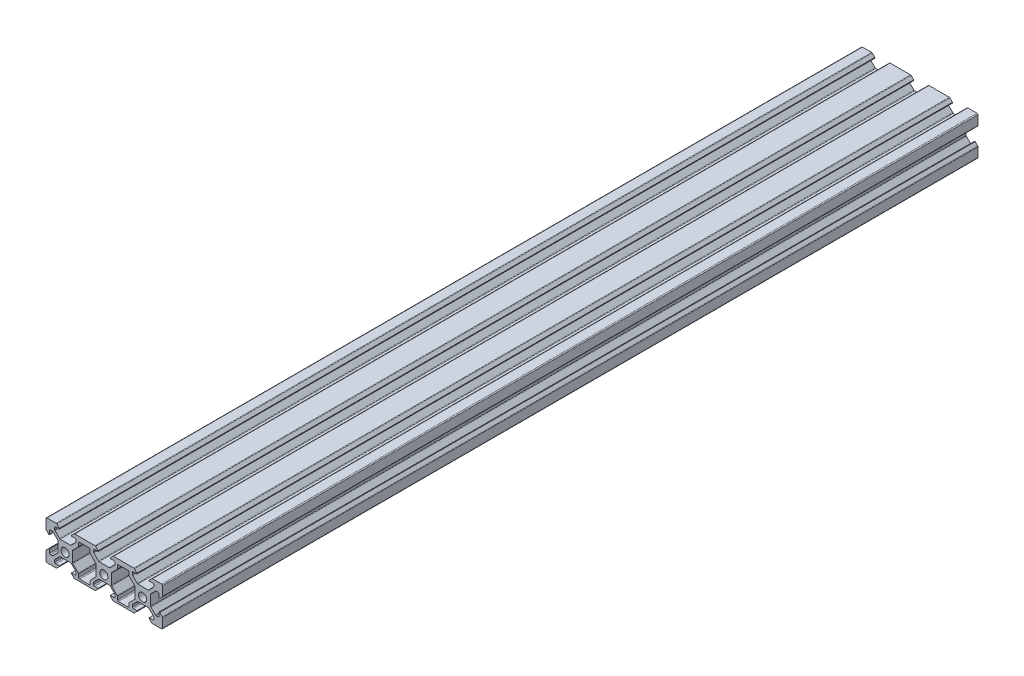
SolidWorks part; units mm, degrees
ref_plane "Front Plane" through (0, 0, 0) normal (0, 0, 1) x (1, 0, 0)
ref_plane "Top Plane" through (0, 0, 0) normal (0, 1, 0) x (1, 0, 0)
ref_plane "Right Plane" through (0, 0, 0) normal (1, 0, 0) x (0, 0, -1)
sketch "Sketch1" plane through (0, 0, 0) normal (0, 0, 1) x (1, 0, 0)
  line L24 (-13, 7.7) -> (-13, 6.1464)
  line L25 (-12.5, 8.2) -> (-7.5, 8.2)
  line L26 (-7, 6.1464) -> (-7, 7.7)
  line L27 (-6.8536, 5.7929) -> (-4.0464, 2.9858)
  line L28 (-3.9, 2.6322) -> (-3.9, -2.6322)
  line L29 (-15.9536, 2.9858) -> (-13.1464, 5.7929)
  line L30 (-16.1, -2.6322) -> (-16.1, 2.6322)
  line L31 (-13.1464, -5.7929) -> (-15.9536, -2.9858)
  line L32 (-13, -6.1464) -> (-13, -7.7)
  line L33 (-7.5, -8.2) -> (-12.5, -8.2)
  line L34 (-7, -7.7) -> (-7, -6.1464)
  line L35 (-4.0464, -2.9858) -> (-6.8536, -5.7929)
  line L36 (12.5, -8.2) -> (7.5, -8.2)
  line L37 (7, -6.1464) -> (7, -7.7)
  line L38 (6.8536, -5.7929) -> (4.0464, -2.9858)
  line L39 (3.9, -2.6322) -> (3.9, 2.6322)
  line L40 (4.0464, 2.9858) -> (6.8536, 5.7929)
  line L41 (7, 7.7) -> (7, 6.1464)
  line L42 (7.5, 8.2) -> (12.5, 8.2)
  line L43 (13, 6.1464) -> (13, 7.7)
  line L44 (13.1464, 5.7929) -> (15.9536, 2.9858)
  line L45 (16.1, 2.6322) -> (16.1, -2.6322)
  line L46 (15.9536, -2.9858) -> (13.1464, -5.7929)
  line L47 (13, -7.7) -> (13, -6.1464)
  line L200 (-22.4092, -3.2009) -> (-17.1447, -3.2009)
  line L201 (-16.7912, -3.3473) -> (-14.4234, -5.7151)
  line L202 (-14.277, -6.0686) -> (-14.277, -7.0009)
  line L203 (-14.777, -7.5009) -> (-16.652, -7.5009)
  line L204 (-16.652, -7.5009) -> (-16.652, -7.8459)
  line L205 (-16.652, -7.8459) -> (-15.3434, -9.1544)
  line L206 (-14.9898, -9.3009) -> (-4.5641, -9.3009)
  line L207 (-4.2105, -9.1544) -> (-2.902, -7.8459)
  line L208 (-2.902, -7.8459) -> (-2.902, -7.5009)
  line L209 (-2.902, -7.5009) -> (-4.777, -7.5009)
  line L210 (-5.277, -7.0009) -> (-5.277, -6.0686)
  line L211 (-5.1305, -5.7151) -> (-2.7627, -3.3473)
  line L212 (-2.4092, -3.2009) -> (2.8553, -3.2009)
  line L213 (3.2088, -3.3473) -> (5.5766, -5.7151)
  line L214 (5.723, -6.0686) -> (5.723, -7.0009)
  line L215 (5.223, -7.5009) -> (3.348, -7.5009)
  line L216 (3.348, -7.5009) -> (3.348, -7.8459)
  line L217 (3.348, -7.8459) -> (4.6566, -9.1544)
  line L218 (5.0102, -9.3009) -> (15.4359, -9.3009)
  line L219 (15.7895, -9.1544) -> (17.098, -7.8459)
  line L220 (17.098, -7.8459) -> (17.098, -7.5009)
  line L221 (17.098, -7.5009) -> (15.223, -7.5009)
  line L222 (14.723, -7.0009) -> (14.723, -6.0686)
  line L223 (14.8695, -5.7151) -> (17.2373, -3.3473)
  line L224 (17.5908, -3.2009) -> (22.8553, -3.2009)
  line L225 (23.2088, -3.3473) -> (25.5766, -5.7151)
  line L226 (25.723, -6.0686) -> (25.723, -7.0009)
  line L227 (25.223, -7.5009) -> (23.348, -7.5009)
  line L228 (23.348, -7.5009) -> (23.348, -7.8459)
  line L229 (23.348, -7.8459) -> (24.6566, -9.1544)
  line L230 (25.0102, -9.3009) -> (29.723, -9.3009)
  line L231 (30.223, -8.8009) -> (30.223, -4.088)
  line L232 (30.0766, -3.7344) -> (28.768, -2.4259)
  line L233 (28.768, -2.4259) -> (28.423, -2.4259)
  line L234 (28.423, -2.4259) -> (28.423, -4.3009)
  line L235 (27.923, -4.8009) -> (26.9908, -4.8009)
  line L236 (26.6373, -4.6544) -> (24.2695, -2.2866)
  line L237 (24.123, -1.9331) -> (24.123, 3.3314)
  line L238 (24.2695, 3.6849) -> (26.6373, 6.0527)
  line L239 (26.9908, 6.1991) -> (27.923, 6.1991)
  line L240 (28.423, 5.6991) -> (28.423, 3.8241)
  line L241 (28.423, 3.8241) -> (28.768, 3.8241)
  line L242 (28.768, 3.8241) -> (30.0766, 5.1327)
  line L243 (30.223, 5.4863) -> (30.223, 10.1991)
  line L244 (29.723, 10.6991) -> (25.0102, 10.6991)
  line L245 (24.6566, 10.5527) -> (23.348, 9.2441)
  line L246 (23.348, 9.2441) -> (23.348, 8.8991)
  line L247 (23.348, 8.8991) -> (25.223, 8.8991)
  line L248 (25.723, 8.3991) -> (25.723, 7.4669)
  line L249 (25.5766, 7.1134) -> (23.2088, 4.7456)
  line L250 (22.8553, 4.5991) -> (17.5908, 4.5991)
  line L251 (17.2373, 4.7456) -> (14.8695, 7.1134)
  line L252 (14.723, 7.4669) -> (14.723, 8.3991)
  line L253 (15.223, 8.8991) -> (17.098, 8.8991)
  line L254 (17.098, 8.8991) -> (17.098, 9.2441)
  line L255 (17.098, 9.2441) -> (15.7895, 10.5527)
  line L256 (15.4359, 10.6991) -> (5.0102, 10.6991)
  line L257 (4.6566, 10.5527) -> (3.348, 9.2441)
  line L258 (3.348, 9.2441) -> (3.348, 8.8991)
  line L259 (3.348, 8.8991) -> (5.223, 8.8991)
  line L260 (5.723, 8.3991) -> (5.723, 7.4669)
  line L261 (5.5766, 7.1134) -> (3.2088, 4.7456)
  line L262 (2.8553, 4.5991) -> (-2.4092, 4.5991)
  line L263 (-2.7627, 4.7456) -> (-5.1305, 7.1134)
  line L264 (-5.277, 7.4669) -> (-5.277, 8.3991)
  line L265 (-4.777, 8.8991) -> (-2.902, 8.8991)
  line L266 (-2.902, 8.8991) -> (-2.902, 9.2441)
  line L267 (-2.902, 9.2441) -> (-4.2105, 10.5527)
  line L268 (-4.5641, 10.6991) -> (-14.9898, 10.6991)
  line L269 (-15.3434, 10.5527) -> (-16.652, 9.2441)
  line L270 (-16.652, 9.2441) -> (-16.652, 8.8991)
  line L271 (-16.652, 8.8991) -> (-14.777, 8.8991)
  line L272 (-14.277, 8.3991) -> (-14.277, 7.4669)
  line L273 (-14.4234, 7.1134) -> (-16.7912, 4.7456)
  line L274 (-17.1447, 4.5991) -> (-22.4092, 4.5991)
  line L275 (-22.7627, 4.7456) -> (-25.1305, 7.1134)
  line L276 (-25.277, 7.4669) -> (-25.277, 8.3991)
  line L277 (-24.777, 8.8991) -> (-22.902, 8.8991)
  line L278 (-22.902, 8.8991) -> (-22.902, 9.2441)
  line L279 (-22.902, 9.2441) -> (-24.2105, 10.5527)
  line L280 (-24.5641, 10.6991) -> (-29.277, 10.6991)
  line L281 (-29.777, 10.1991) -> (-29.777, 5.4863)
  line L282 (-29.6305, 5.1327) -> (-28.322, 3.8241)
  line L283 (-28.322, 3.8241) -> (-27.977, 3.8241)
  line L284 (-27.977, 3.8241) -> (-27.977, 5.6991)
  line L285 (-27.477, 6.1991) -> (-26.5447, 6.1991)
  line L286 (-26.1912, 6.0527) -> (-23.8234, 3.6849)
  line L287 (-23.677, 3.3314) -> (-23.677, -1.9331)
  line L288 (-23.8234, -2.2866) -> (-26.1912, -4.6544)
  line L289 (-26.5447, -4.8009) -> (-27.477, -4.8009)
  line L290 (-27.977, -4.3009) -> (-27.977, -2.4259)
  line L291 (-27.977, -2.4259) -> (-28.322, -2.4259)
  line L292 (-28.322, -2.4259) -> (-29.6305, -3.7344)
  line L293 (-29.777, -4.088) -> (-29.777, -8.8009)
  line L294 (-29.277, -9.3009) -> (-24.5641, -9.3009)
  line L295 (-24.2105, -9.1544) -> (-22.902, -7.8459)
  line L296 (-22.902, -7.8459) -> (-22.902, -7.5009)
  line L297 (-22.902, -7.5009) -> (-24.777, -7.5009)
  line L298 (-25.277, -7.0009) -> (-25.277, -6.0686)
  line L299 (-25.1305, -5.7151) -> (-22.7627, -3.3473)
  arc A27 (-13.1464, 5.7929) -> (-13, 6.1464) centre (-13.5, 6.1464) ccw
  arc A28 (-12.5, 8.2) -> (-13, 7.7) centre (-12.5, 7.7) ccw
  arc A29 (-7, 7.7) -> (-7.5, 8.2) centre (-7.5, 7.7) ccw
  arc A30 (-7, 6.1464) -> (-6.8536, 5.7929) centre (-6.5, 6.1464) ccw
  arc A31 (-3.9, 2.6322) -> (-4.0464, 2.9858) centre (-4.4, 2.6322) ccw
  arc A32 (-15.9536, 2.9858) -> (-16.1, 2.6322) centre (-15.6, 2.6322) ccw
  circle A33 centre (-20, 0) radius 2.1
  arc A34 (-16.1, -2.6322) -> (-15.9536, -2.9858) centre (-15.6, -2.6322) ccw
  arc A35 (-13, -6.1464) -> (-13.1464, -5.7929) centre (-13.5, -6.1464) ccw
  arc A36 (-13, -7.7) -> (-12.5, -8.2) centre (-12.5, -7.7) ccw
  arc A37 (-7.5, -8.2) -> (-7, -7.7) centre (-7.5, -7.7) ccw
  arc A38 (-6.8536, -5.7929) -> (-7, -6.1464) centre (-6.5, -6.1464) ccw
  arc A39 (-4.0464, -2.9858) -> (-3.9, -2.6322) centre (-4.4, -2.6322) ccw
  circle A40 centre (0, 0) radius 2.1
  arc A41 (7, -7.7) -> (7.5, -8.2) centre (7.5, -7.7) ccw
  arc A42 (7, -6.1464) -> (6.8536, -5.7929) centre (6.5, -6.1464) ccw
  arc A43 (3.9, -2.6322) -> (4.0464, -2.9858) centre (4.4, -2.6322) ccw
  arc A44 (4.0464, 2.9858) -> (3.9, 2.6322) centre (4.4, 2.6322) ccw
  arc A45 (6.8536, 5.7929) -> (7, 6.1464) centre (6.5, 6.1464) ccw
  arc A46 (7.5, 8.2) -> (7, 7.7) centre (7.5, 7.7) ccw
  arc A47 (13, 7.7) -> (12.5, 8.2) centre (12.5, 7.7) ccw
  arc A48 (13, 6.1464) -> (13.1464, 5.7929) centre (13.5, 6.1464) ccw
  arc A49 (16.1, 2.6322) -> (15.9536, 2.9858) centre (15.6, 2.6322) ccw
  arc A50 (15.9536, -2.9858) -> (16.1, -2.6322) centre (15.6, -2.6322) ccw
  arc A51 (13.1464, -5.7929) -> (13, -6.1464) centre (13.5, -6.1464) ccw
  arc A52 (12.5, -8.2) -> (13, -7.7) centre (12.5, -7.7) ccw
  circle A53 centre (20, 0) radius 2.1
  arc A136 (-22.4092, -3.2009) -> (-22.7627, -3.3473) centre (-22.4092, -3.7009) ccw
  arc A137 (-16.7912, -3.3473) -> (-17.1447, -3.2009) centre (-17.1447, -3.7009) ccw
  arc A138 (-14.277, -6.0686) -> (-14.4234, -5.7151) centre (-14.777, -6.0686) ccw
  arc A139 (-14.777, -7.5009) -> (-14.277, -7.0009) centre (-14.777, -7.0009) ccw
  arc A140 (-15.3434, -9.1544) -> (-14.9898, -9.3009) centre (-14.9898, -8.8009) ccw
  arc A141 (-4.5641, -9.3009) -> (-4.2105, -9.1544) centre (-4.5641, -8.8009) ccw
  arc A142 (-5.277, -7.0009) -> (-4.777, -7.5009) centre (-4.777, -7.0009) ccw
  arc A143 (-5.1305, -5.7151) -> (-5.277, -6.0686) centre (-4.777, -6.0686) ccw
  arc A144 (-2.4092, -3.2009) -> (-2.7627, -3.3473) centre (-2.4092, -3.7009) ccw
  arc A145 (3.2088, -3.3473) -> (2.8553, -3.2009) centre (2.8553, -3.7009) ccw
  arc A146 (5.723, -6.0686) -> (5.5766, -5.7151) centre (5.223, -6.0686) ccw
  arc A147 (5.223, -7.5009) -> (5.723, -7.0009) centre (5.223, -7.0009) ccw
  arc A148 (4.6566, -9.1544) -> (5.0102, -9.3009) centre (5.0102, -8.8009) ccw
  arc A149 (15.4359, -9.3009) -> (15.7895, -9.1544) centre (15.4359, -8.8009) ccw
  arc A150 (14.723, -7.0009) -> (15.223, -7.5009) centre (15.223, -7.0009) ccw
  arc A151 (14.8695, -5.7151) -> (14.723, -6.0686) centre (15.223, -6.0686) ccw
  arc A152 (17.5908, -3.2009) -> (17.2373, -3.3473) centre (17.5908, -3.7009) ccw
  arc A153 (23.2088, -3.3473) -> (22.8553, -3.2009) centre (22.8553, -3.7009) ccw
  arc A154 (25.723, -6.0686) -> (25.5766, -5.7151) centre (25.223, -6.0686) ccw
  arc A155 (25.223, -7.5009) -> (25.723, -7.0009) centre (25.223, -7.0009) ccw
  arc A156 (24.6566, -9.1544) -> (25.0102, -9.3009) centre (25.0102, -8.8009) ccw
  arc A157 (29.723, -9.3009) -> (30.223, -8.8009) centre (29.723, -8.8009) ccw
  arc A158 (30.223, -4.088) -> (30.0766, -3.7344) centre (29.723, -4.088) ccw
  arc A159 (27.923, -4.8009) -> (28.423, -4.3009) centre (27.923, -4.3009) ccw
  arc A160 (26.6373, -4.6544) -> (26.9908, -4.8009) centre (26.9908, -4.3009) ccw
  arc A161 (24.123, -1.9331) -> (24.2695, -2.2866) centre (24.623, -1.9331) ccw
  arc A162 (24.2695, 3.6849) -> (24.123, 3.3314) centre (24.623, 3.3314) ccw
  arc A163 (26.9908, 6.1991) -> (26.6373, 6.0527) centre (26.9908, 5.6991) ccw
  arc A164 (28.423, 5.6991) -> (27.923, 6.1991) centre (27.923, 5.6991) ccw
  arc A165 (30.0766, 5.1327) -> (30.223, 5.4863) centre (29.723, 5.4863) ccw
  arc A166 (30.223, 10.1991) -> (29.723, 10.6991) centre (29.723, 10.1991) ccw
  arc A167 (25.0102, 10.6991) -> (24.6566, 10.5527) centre (25.0102, 10.1991) ccw
  arc A168 (25.723, 8.3991) -> (25.223, 8.8991) centre (25.223, 8.3991) ccw
  arc A169 (25.5766, 7.1134) -> (25.723, 7.4669) centre (25.223, 7.4669) ccw
  arc A170 (22.8553, 4.5991) -> (23.2088, 4.7456) centre (22.8553, 5.0991) ccw
  arc A171 (17.2373, 4.7456) -> (17.5908, 4.5991) centre (17.5908, 5.0991) ccw
  arc A172 (14.723, 7.4669) -> (14.8695, 7.1134) centre (15.223, 7.4669) ccw
  arc A173 (15.223, 8.8991) -> (14.723, 8.3991) centre (15.223, 8.3991) ccw
  arc A174 (15.7895, 10.5527) -> (15.4359, 10.6991) centre (15.4359, 10.1991) ccw
  arc A175 (5.0102, 10.6991) -> (4.6566, 10.5527) centre (5.0102, 10.1991) ccw
  arc A176 (5.723, 8.3991) -> (5.223, 8.8991) centre (5.223, 8.3991) ccw
  arc A177 (5.5766, 7.1134) -> (5.723, 7.4669) centre (5.223, 7.4669) ccw
  arc A178 (2.8553, 4.5991) -> (3.2088, 4.7456) centre (2.8553, 5.0991) ccw
  arc A179 (-2.7627, 4.7456) -> (-2.4092, 4.5991) centre (-2.4092, 5.0991) ccw
  arc A180 (-5.277, 7.4669) -> (-5.1305, 7.1134) centre (-4.777, 7.4669) ccw
  arc A181 (-4.777, 8.8991) -> (-5.277, 8.3991) centre (-4.777, 8.3991) ccw
  arc A182 (-4.2105, 10.5527) -> (-4.5641, 10.6991) centre (-4.5641, 10.1991) ccw
  arc A183 (-14.9898, 10.6991) -> (-15.3434, 10.5527) centre (-14.9898, 10.1991) ccw
  arc A184 (-14.277, 8.3991) -> (-14.777, 8.8991) centre (-14.777, 8.3991) ccw
  arc A185 (-14.4234, 7.1134) -> (-14.277, 7.4669) centre (-14.777, 7.4669) ccw
  arc A186 (-17.1447, 4.5991) -> (-16.7912, 4.7456) centre (-17.1447, 5.0991) ccw
  arc A187 (-22.7627, 4.7456) -> (-22.4092, 4.5991) centre (-22.4092, 5.0991) ccw
  arc A188 (-25.277, 7.4669) -> (-25.1305, 7.1134) centre (-24.777, 7.4669) ccw
  arc A189 (-24.777, 8.8991) -> (-25.277, 8.3991) centre (-24.777, 8.3991) ccw
  arc A190 (-24.2105, 10.5527) -> (-24.5641, 10.6991) centre (-24.5641, 10.1991) ccw
  arc A191 (-29.277, 10.6991) -> (-29.777, 10.1991) centre (-29.277, 10.1991) ccw
  arc A192 (-29.777, 5.4863) -> (-29.6305, 5.1327) centre (-29.277, 5.4863) ccw
  arc A193 (-27.477, 6.1991) -> (-27.977, 5.6991) centre (-27.477, 5.6991) ccw
  arc A194 (-26.1912, 6.0527) -> (-26.5447, 6.1991) centre (-26.5447, 5.6991) ccw
  arc A195 (-23.677, 3.3314) -> (-23.8234, 3.6849) centre (-24.177, 3.3314) ccw
  arc A196 (-23.8234, -2.2866) -> (-23.677, -1.9331) centre (-24.177, -1.9331) ccw
  arc A197 (-26.5447, -4.8009) -> (-26.1912, -4.6544) centre (-26.5447, -4.3009) ccw
  arc A198 (-27.977, -4.3009) -> (-27.477, -4.8009) centre (-27.477, -4.3009) ccw
  arc A199 (-29.6305, -3.7344) -> (-29.777, -4.088) centre (-29.277, -4.088) ccw
  arc A200 (-29.777, -8.8009) -> (-29.277, -9.3009) centre (-29.277, -8.8009) ccw
  arc A201 (-24.5641, -9.3009) -> (-24.2105, -9.1544) centre (-24.5641, -8.8009) ccw
  arc A202 (-25.277, -7.0009) -> (-24.777, -7.5009) centre (-24.777, -7.0009) ccw
  arc A203 (-25.1305, -5.7151) -> (-25.277, -6.0686) centre (-24.777, -6.0686) ccw
extrude "Boss-Extrude1" add sketch "Sketch1" along normal blind 420
